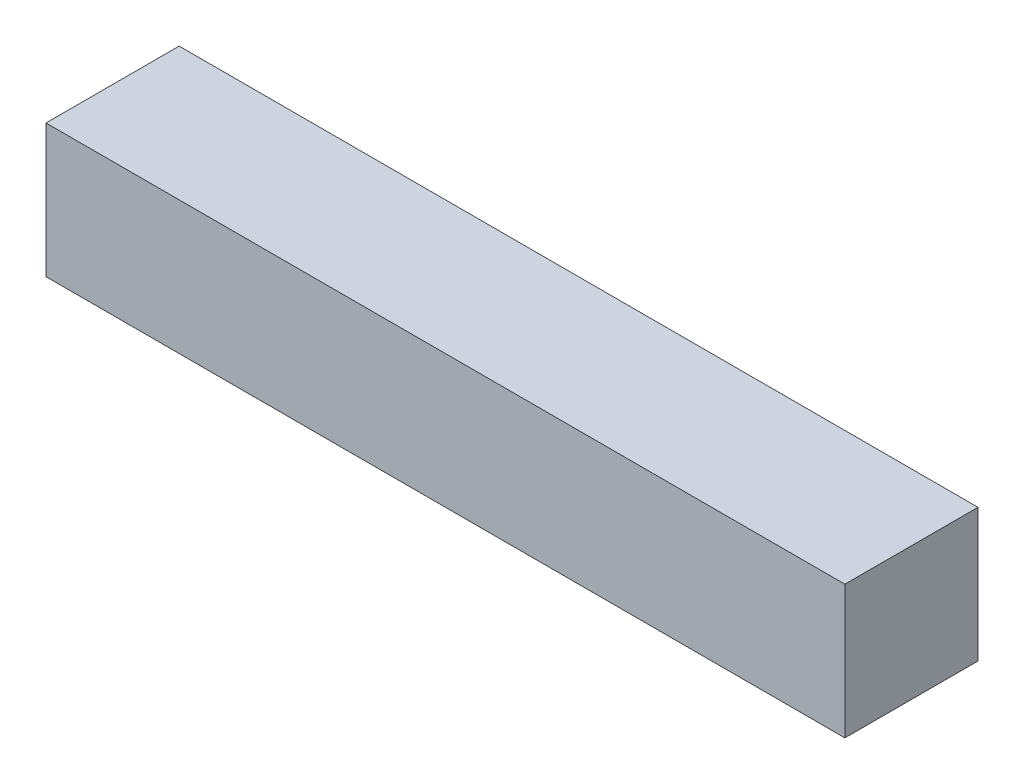
SolidWorks part; units mm, degrees
ref_plane "Front Plane" through (0, 0, 0) normal (0, 0, 1) x (1, 0, 0)
ref_plane "Top Plane" through (0, 0, 0) normal (0, 1, 0) x (1, 0, 0)
ref_plane "Right Plane" through (0, 0, 0) normal (1, 0, 0) x (0, 0, -1)
sketch "Sketch1" plane through (0, 0, 0) normal (1, 0, 0) x (0, 0, -1)
  line L1 (0, 0) -> (25.4, 0)
  line L2 (0, 0) -> (0, -25.4)
  line L3 (0, -25.4) -> (25.4, -25.4)
  line L4 (25.4, 0) -> (25.4, -25.4)
  dimension "D1" = 25.4
  dimension "D2" = 25.4
extrude "Boss-Extrude1" add sketch "Sketch1" along normal blind 152.4
